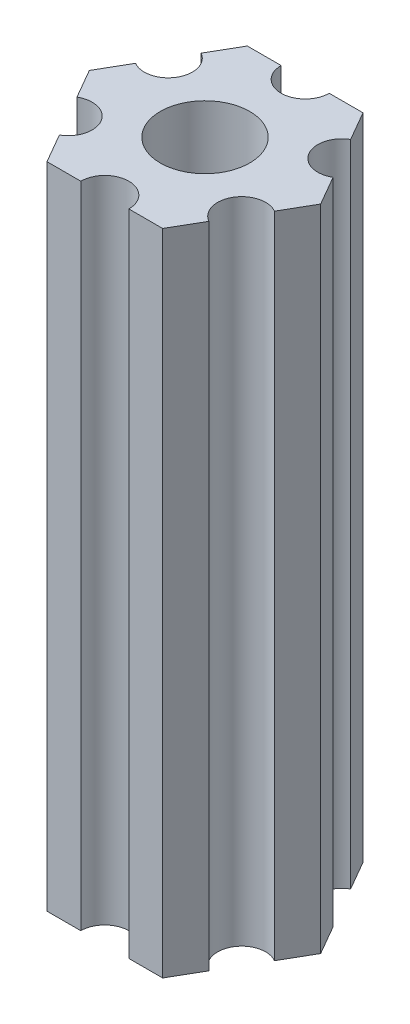
SolidWorks part; units mm, degrees
ref_plane "Plano frontal" through (0, 0, 0) normal (0, 0, 1) x (1, 0, 0)
ref_plane "Plano superior" through (0, 0, 0) normal (0, 1, 0) x (1, 0, 0)
ref_plane "Plano direito" through (0, 0, 0) normal (1, 0, 0) x (0, 0, -1)
ref_plane "Plano1" through (0, -34.5, 0) normal (0, -1, 0) x (1, 0, 0)
sketch "Esboço1" plane through (0, -34.5, 0) normal (0, -1, 0) x (1, 0, 0)
  line L0 (77.0627, 17.174) -> (78.1169, 19)
  line L1 (78.1169, 19) -> (77.0627, 20.826)
  line L2 (75.5627, 23.424) -> (74.5084, 25.25)
  line L3 (74.5084, 25.25) -> (72.4, 25.25)
  line L4 (69.4, 25.25) -> (67.2916, 25.25)
  line L5 (67.2916, 25.25) -> (66.2373, 23.424)
  line L6 (64.7373, 20.826) -> (63.6831, 19)
  line L7 (63.6831, 19) -> (64.7373, 17.174)
  line L8 (66.2373, 14.576) -> (67.2916, 12.75)
  line L9 (67.2916, 12.75) -> (69.4, 12.75)
  line L10 (72.4, 12.75) -> (74.5084, 12.75)
  line L11 (74.5084, 12.75) -> (75.5627, 14.576)
  circle A0 centre (70.9, 19) radius 2.79
  arc A1 (77.0627, 20.826) -> (75.5627, 23.424) centre (76.3127, 22.125) cw
  arc A2 (72.4, 25.25) -> (69.4, 25.25) centre (70.9, 25.25) cw
  arc A3 (66.2373, 23.424) -> (64.7373, 20.826) centre (65.4873, 22.125) cw
  arc A4 (64.7373, 17.174) -> (66.2373, 14.576) centre (65.4873, 15.875) cw
  arc A5 (69.4, 12.75) -> (72.4, 12.75) centre (70.9, 12.75) cw
  arc A6 (75.5627, 14.576) -> (77.0627, 17.174) centre (76.3127, 15.875) cw
extrude "Ressalto-extrusão1" add sketch "Esboço1" against normal blind 40.5
